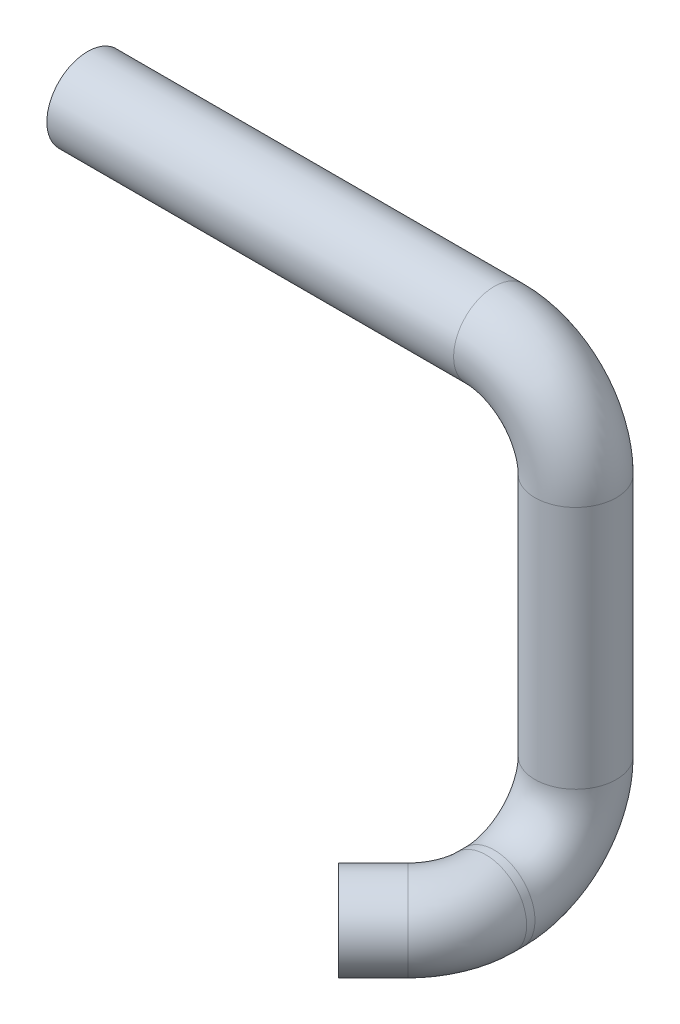
SolidWorks part; units mm, degrees
ref_plane "Front Plane" through (0, 0, 0) normal (0, 0, 1) x (1, 0, 0)
ref_plane "Top Plane" through (0, 0, 0) normal (0, 1, 0) x (1, 0, 0)
ref_plane "Right Plane" through (0, 0, 0) normal (1, 0, 0) x (0, 0, -1)
sketch3d "3DSketch1"
  line L0 (0, 0, 0) -> (31.75, 0, 0)
  line L1 (38.1, -6.35, 0) -> (38.1, -25.4, 0)
  line L2 (36.3145, -31.75, 11.3105) -> (33.6099, -31.75, 14.0151)
  line L3 (38.1, -31.75, 6.35) -> (38.1, -31.75, 7)
  line L4 (38.1, -31.75, 7) -> (38.1, -31.75, 30.0378) construction
  line L5 (36.3145, -31.75, 11.3105) -> (36.3145, -18.8737, 11.3105) construction
  arc A0 (31.75, 0, 0) -> (38.1, -6.35, 0) centre (31.75, -6.35, 0) ccw
  arc A1 (38.1, -25.4, 0) -> (38.1, -31.75, 6.35) centre (38.1, -25.4, 6.35) ccw
  arc A2 (38.1, -31.75, 7) -> (36.3145, -31.75, 11.3105) centre (32.004, -31.75, 7) ccw
  point P7 (38.1, 0, 0)
  point P8 (31.75, -6.35, -6.35)
  point P12 (31.75, -25.4, 6.35)
  point P15 (38.1, -31.75, 9.525)
  point P16 (32.004, -37.846, 7)
  dimension "D4" = 6.35
  dimension "D3" = 3.175
  dimension "D5" = 6.35
  dimension "D6" = 6.096
  dimension "D1" = 38.1
  dimension "D2" = 25.4
  dimension "D7" = 45
  dimension "D8" = 90
sketch "Sketch2" plane through (0, 0, 0) normal (1, 0, 0) x (0, 0, -1)
  circle A0 centre (0, 0) radius 3.175
  circle A1 centre (0, 0) radius 2.286
  dimension "D1" = 6.35
  dimension "D2" = 0.889
sweep "Sweep1" add profiles "Sketch2" path "3DSketch1"
ref_plane "Plane1" through (0, -25.4, 0) normal (0, 1, 0) x (1, 0, 0)
